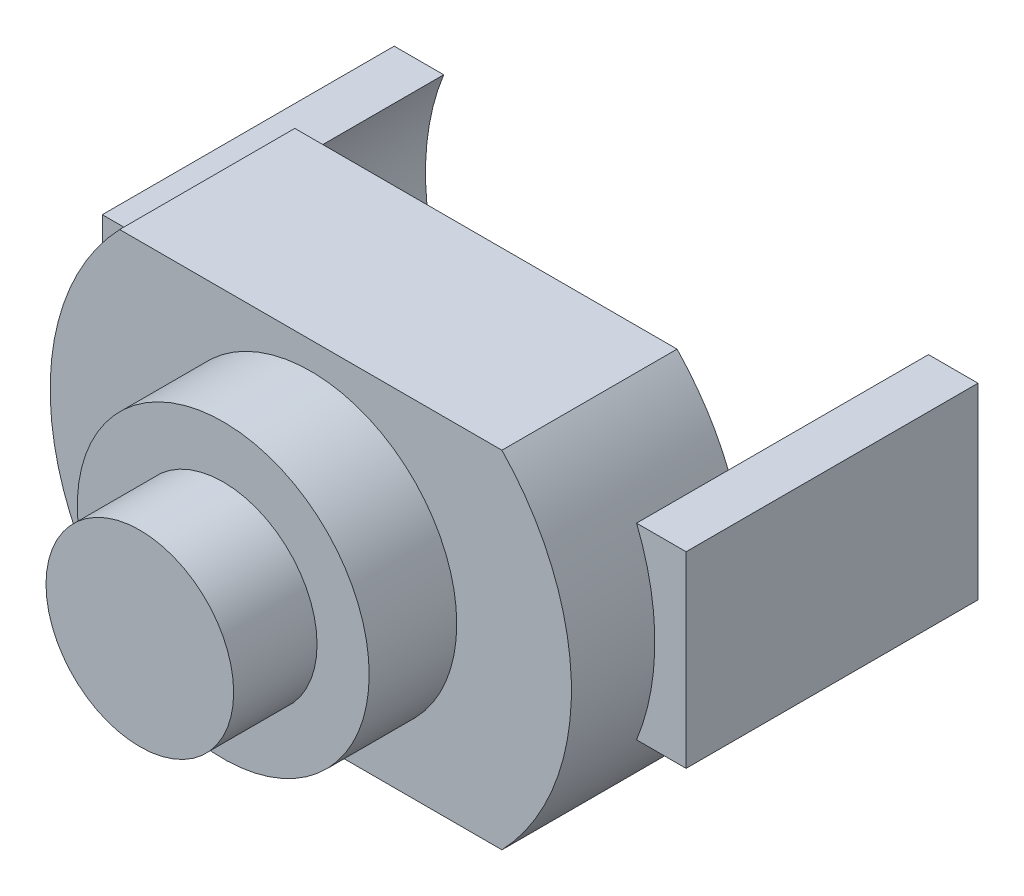
SolidWorks part; units mm, degrees
ref_plane "前视基准面" through (0, 0, 0) normal (0, 0, 1) x (1, 0, 0)
ref_plane "上视基准面" through (0, 0, 0) normal (0, 1, 0) x (1, 0, 0)
ref_plane "右视基准面" through (0, 0, 0) normal (1, 0, 0) x (0, 0, -1)
sketch "草图1" plane through (0, 0, 0) normal (0, 0, 1) x (1, 0, 0)
  line L0 (-7, -4.15) -> (7, -4.15)
  line L1 (-7, -4.15) -> (-7, 4.15)
  line L2 (-7, 4.15) -> (7, 4.15)
  line L3 (7, -4.15) -> (7, 4.15)
  line L4 (-6.25, -4.15) -> (6.25, -4.15)
  line L5 (-6.25, -4.15) -> (-6.25, 4.15)
  line L6 (-6.25, 4.15) -> (6.25, 4.15)
  line L7 (6.25, -4.15) -> (6.25, 4.15)
  line L8 (-6.25, -4.15) -> (6.25, 4.15) construction
  line L9 (-6.25, 4.15) -> (6.25, -4.15) construction
  arc A0 (-4.5833, 4.15) -> (-4.5833, -4.15) centre (-0.25, 0) ccw
  arc A1 (4.5833, 4.15) -> (4.5833, -4.15) centre (0.25, 0) cw
  point P4 (0, 0)
  point P9 (0, 4.15)
  point P11 (7, 0)
extrude "凸台-拉伸1" add sketch "草图1" along normal blind 4.2 contours A1 L6 A0 L4
sketch "草图2" plane through (0, 0, 4.2) normal (0, 0, 1) x (1, 0, 0)
  circle A0 centre (0, 0) radius 3.5
  dimension "D1" = 7
extrude "凸台-拉伸2" add sketch "草图2" along normal blind 2.1
sketch "草图3" plane through (0, 0, 6.3) normal (0, 0, 1) x (1, 0, 0)
  circle A0 centre (0, 0) radius 2.25
  dimension "D1" = 4.5
extrude "凸台-拉伸3" add sketch "草图3" along normal blind 2
sketch "草图4" plane through (0, 0, 4.2) normal (0, 0, 1) x (1, 0, 0)
  line L0 (5.8121, 2.25) -> (7, 2.25)
  line L1 (-7, 2.25) -> (-5.8121, 2.25)
  line L2 (-7, 2.25) -> (-7, -2.25)
  line L3 (-7, -2.25) -> (-5.8121, -2.25)
  line L4 (7, 2.25) -> (7, -2.25)
  line L5 (-7, 2.25) -> (-5.9383, 1.9087) construction
  line L6 (-7, -2.25) -> (-5.9383, -1.9087) construction
  line L7 (5.9383, -1.9087) -> (7, -2.25) construction
  line L8 (-4.5833, -4.15) -> (4.5833, -4.15)
  line L9 (4.5833, 4.15) -> (-4.5833, 4.15)
  line L10 (-4.5833, -4.15) -> (4.5833, -4.15)
  line L12 (5.9383, 1.9087) -> (7, 2.25) construction
  line L13 (5.8121, -2.25) -> (7, -2.25)
  arc A2 (4.5833, -4.15) -> (4.5833, 4.15) centre (0.25, 0) ccw
  arc A3 (-4.5833, 4.15) -> (-4.5833, -4.15) centre (-0.25, 0) ccw
  arc A4 (5.8121, -2.25) -> (5.8121, 2.25) centre (0.25, 0) ccw
  arc A5 (-5.8121, 2.25) -> (-4.5833, -4.15) centre (-0.25, 0) ccw
  point P0 (0, 0)
  arc M8 (4.5833, -4.15) -> (4.5833, 4.15) centre (0.25, 0) ccw
  arc M10 (-4.5833, 4.15) -> (-4.5833, -4.15) centre (-0.25, 0) ccw
  dimension "D1" = 4.5
  dimension "D2" = 14
  dimension "D3" = 0
extrude "凸台-拉伸4" add sketch "草图4" against normal blind 7 from offset 2 contours L2 L3 L1 M10 | L13 L4 L0 M8
